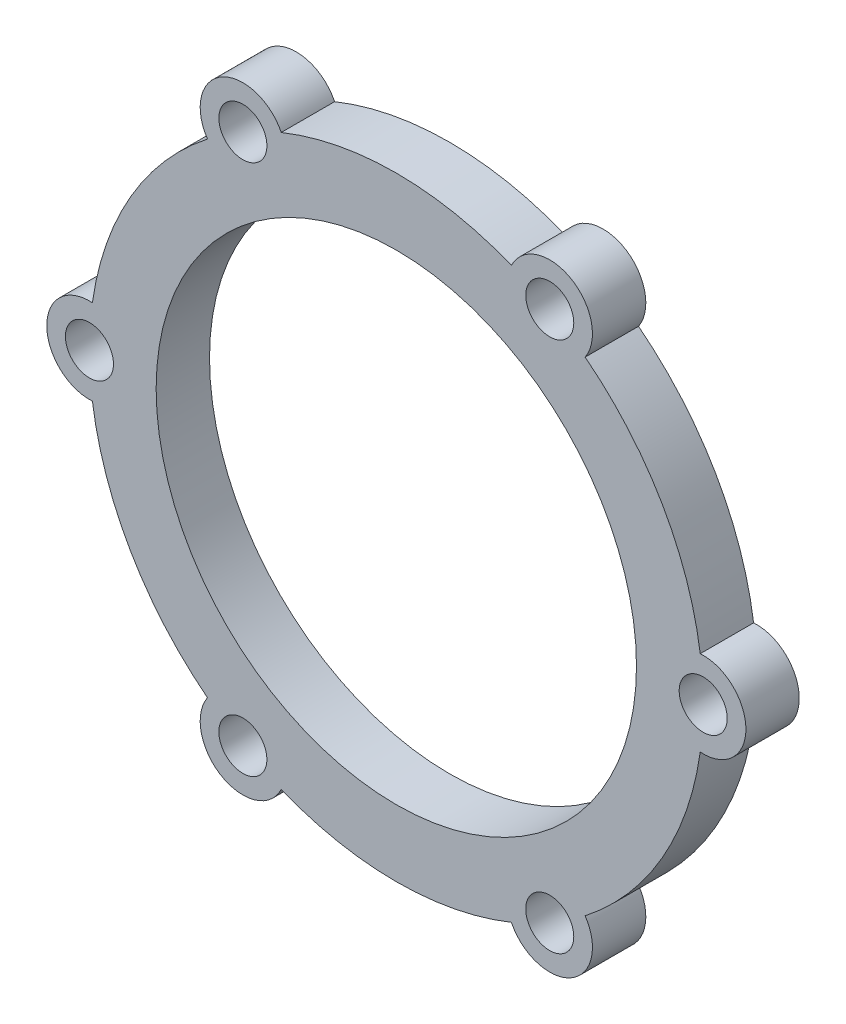
SolidWorks part; units mm, degrees
ref_plane "Płaszczyzna przednia" through (0, 0, 0) normal (0, 0, 1) x (1, 0, 0)
ref_plane "Płaszczyzna górna" through (0, 0, 0) normal (0, 1, 0) x (1, 0, 0)
ref_plane "Płaszczyzna prawa" through (0, 0, 0) normal (1, 0, 0) x (0, 0, -1)
sketch "Szkic1" plane through (0, 0, 0) normal (0, 0, 1) x (1, 0, 0)
  line L0 (0, 0) -> (57.5, 0) construction
  line L1 (0, 0) -> (28.75, 49.7965) construction
  circle A0 centre (0, 0) radius 45
  circle A1 centre (0, 0) radius 57.5
  circle A2 centre (28.75, 49.7965) radius 4.5
  circle A3 centre (28.75, 49.7965) radius 8
  circle A4 centre (57.5, 0) radius 4.5
  circle A5 centre (57.5, 0) radius 8
  circle A6 centre (28.75, -49.7965) radius 4.5
  circle A7 centre (28.75, -49.7965) radius 8
  circle A8 centre (-28.75, -49.7965) radius 4.5
  circle A9 centre (-28.75, -49.7965) radius 8
  circle A10 centre (-57.5, 0) radius 4.5
  circle A11 centre (-57.5, 0) radius 8
  circle A12 centre (-28.75, 49.7965) radius 4.5
  circle A13 centre (-28.75, 49.7965) radius 8
  point P26 (0, 0)
  dimension "D2" = 115
  dimension "D3" = 90
  dimension "D4" = 9
  dimension "D5" = 16
  dimension "D1" = 60
  dimension "D6" = 6
extrude "Dodanie-wyciągnięcie1" add sketch "Szkic1" along normal blind 10 contours A1 A13 A12 | A1 A13 A12 | A13 A1 A11 A9 A7 A5 A3 A0 | A1 A11 A10 | A1 A11 A10 | A1 A3 A2 | A1 A3 A2 | A1 A5 A4 | A1 A5 A4 | A1 A9 A8 | A1 A9 A8 | A1 A7 A6 | A1 A7 A6
